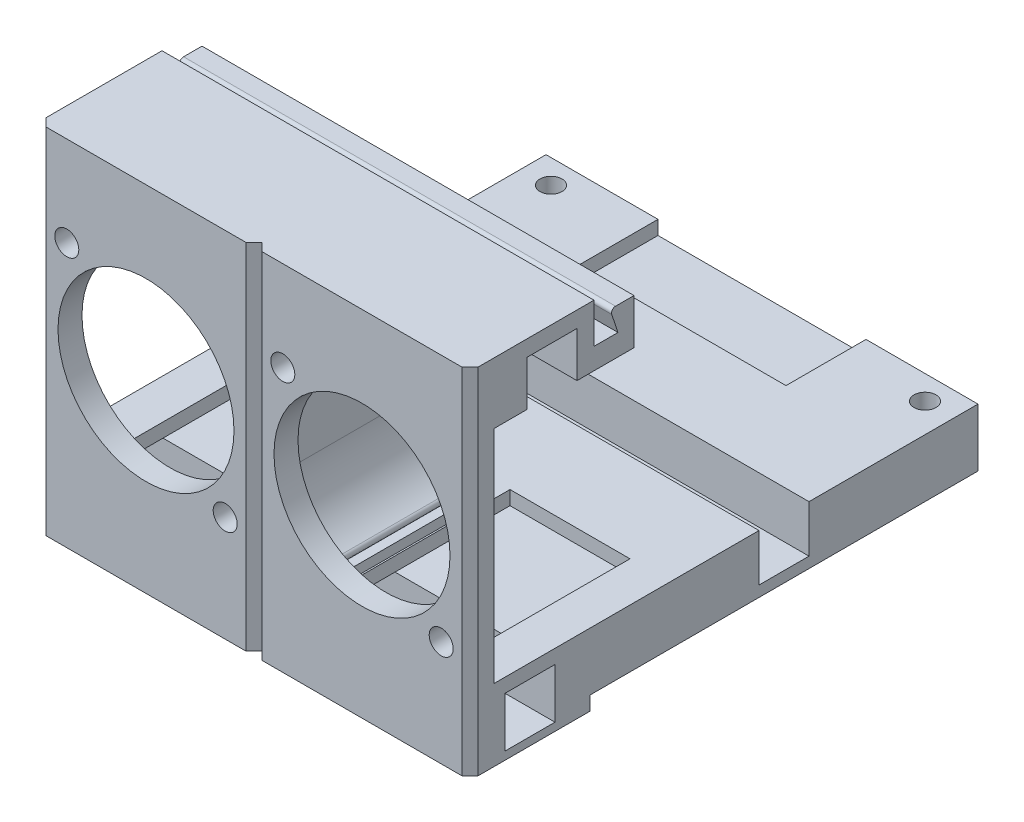
SolidWorks part; units mm, degrees
ref_plane "Front Plane" through (0, 0, 0) normal (0, 0, 1) x (1, 0, 0)
ref_plane "Top Plane" through (0, 0, 0) normal (0, 1, 0) x (1, 0, 0)
ref_plane "Right Plane" through (0, 0, 0) normal (1, 0, 0) x (0, 0, -1)
sketch "Sketch1" plane through (0, 0, 0) normal (0, 1, 0) x (1, 0, 0)
  line L0 (-23.375, 28.75) -> (23.375, 28.75) construction
  line L1 (-27, 31.75) -> (27, 31.75)
  line L2 (-27, 31.75) -> (-27, -31.75)
  line L3 (-27, -31.75) -> (27, -31.75)
  line L4 (27, 31.75) -> (27, -31.75)
  line L5 (-27, 31.75) -> (27, -31.75) construction
  line L6 (-27, -31.75) -> (27, 31.75) construction
  line L11 (0, 0) -> (0, 28.75) construction
  circle A0 centre (-23.375, 28.75) radius 1.375
  circle A1 centre (23.375, 28.75) radius 1.375
  circle A2 centre (0, -5.5) radius 1.375
  point P0 (0, 0)
  dimension "D3" = 2.75
  dimension "D1" = 54
  dimension "D2" = 63.5
  dimension "D4" = 3
  dimension "D5" = 46.75
  dimension "D6" = 34.25
extrude "Boss-Extrude1" add sketch "Sketch1" along normal blind 9
sketch "Sketch2" plane through (0, 9, 0) normal (0, 1, 0) x (1, 0, 0)
  line L0 (27, -31.75) -> (27, 31.75) construction
  line L1 (-27, -31.75) -> (27, -31.75)
  line L2 (-27, -31.75) -> (-27, -28.75)
  line L3 (-27, -28.75) -> (27, -28.75)
  line L4 (27, -31.75) -> (27, -28.75)
  dimension "D1" = 3
extrude "Boss-Extrude2" add sketch "Sketch2" along normal offset from surface (35.25 mm away) 44.25 up to face at (0, 0, 0)
sketch "Sketch3" plane through (0, 0, 31.75) normal (0, 0, 1) x (1, 0, 0)
  line L0 (-27, 9) -> (27, 9) construction
  line L1 (-27, 44.25) -> (-27, 0) construction
  line L2 (27, 44.25) -> (27, 0) construction
  line L3 (0, 10.6) -> (0, 23.1) construction
  line L4 (-27, 10.6) -> (27, 10.6) construction
  line L5 (-23.4, 33) -> (-3.6, 33) construction
  line L6 (-23.4, 33) -> (-23.4, 13.2) construction
  line L7 (-23.4, 13.2) -> (-3.6, 13.2) construction
  line L8 (-3.6, 33) -> (-3.6, 13.2) construction
  line L9 (-23.4, 33) -> (-3.6, 13.2) construction
  line L10 (-23.4, 13.2) -> (-3.6, 33) construction
  line L11 (3.6, 33) -> (23.4, 33) construction
  line L12 (3.6, 33) -> (3.6, 13.2) construction
  line L13 (3.6, 13.2) -> (23.4, 13.2) construction
  line L14 (23.4, 33) -> (23.4, 13.2) construction
  line L15 (3.6, 33) -> (23.4, 13.2) construction
  line L16 (3.6, 13.2) -> (23.4, 33) construction
  line L17 (-2.5, 23.1) -> (-3.6, 23.1) construction
  line L18 (2.5, 23.1) -> (3.6, 23.1) construction
  line L21 (27, 9) -> (-27, 9) construction
  line L22 (-2.5, 23.1) -> (2.5, 23.1) construction
  circle A0 centre (-13.5, 23.1) radius 11
  circle A1 centre (13.5, 23.1) radius 11
  circle A2 centre (-23.4, 33) radius 1.5
  circle A3 centre (-3.6, 13.2) radius 1.5
  circle A4 centre (3.6, 33) radius 1.5
  circle A5 centre (23.4, 13.2) radius 1.5
  point P6 (-13.5, 23.1)
  point P13 (13.5, 23.1)
  dimension "D1" = 3
  dimension "D2" = 22
  dimension "D3" = 19.8
  dimension "D4" = 19.8
  dimension "D5" = 12.5
  dimension "D6" = 1.6
  dimension "D7" = 13.5
  dimension "D8" = 13.5
extrude "Cut-Extrude1" cut sketch "Sketch3" against normal through all
sketch "Sketch4" plane through (0, 0, 0) normal (0, -1, 0) x (-1, 0, 0)
  line L0 (-27, -31.75) -> (-27, 31.75) construction
  line L1 (27, 31.75) -> (-27, 31.75)
  line L2 (27, 31.75) -> (27, -16.75)
  line L3 (27, -16.75) -> (-27, -16.75)
  line L4 (-27, 31.75) -> (-27, -16.75)
  line L5 (27, -31.75) -> (-27, -31.75) construction
  dimension "D1" = 15
extrude "Cut-Extrude2" cut sketch "Sketch4" against normal blind 1.75
sketch "Sketch5" plane through (0, 0, 28.75) normal (0, 0, -1) x (-1, 0, 0)
  line L0 (-13.5, 23.1) -> (13.5, 23.1) construction
  line L1 (0, 9) -> (0, 23.1) construction
  line L2 (-1.25, 23.1) -> (-1.25, 29.8413)
  line L3 (-27, 9) -> (27, 9) construction
  line L15 (-13.5, 23.1) -> (-13.5, 34.1) construction
  line L16 (13.5, 23.1) -> (13.5, 34.1) construction
  line L17 (-13.5, 25.9095) -> (13.5, 25.9095) construction
  line L18 (-1.25, 23.1) -> (-1.25, 19.35)
  line L19 (-5.8167, 10.6) -> (0, 10.6)
  line L20 (1.5, 23.1) -> (1.5, 16.8865)
  line L21 (0, 10.6) -> (0.6, 10.6)
  line L22 (0.6, 10.6) -> (0.6, 13.2)
  line L23 (0.6, 13.2) -> (3.6, 13.2) construction
  line L24 (-1.25, 23.1) -> (0, 23.1) construction
  line L25 (1.5, 23.1) -> (1.5, 25.3221)
  line L26 (9.4, 36.6) -> (-0.6, 36.6)
  line L27 (-0.6, 36.6) -> (-0.6, 33)
  line L28 (-3.6, 33) -> (-0.6, 33) construction
  line L29 (0, 23.1) -> (1.5, 23.1) construction
  arc A13 (-0.8437, 31.8155) -> (-0.6, 33) centre (-3.6, 33) ccw
  circle A16 centre (13.5, 23.1) radius 11 construction
  circle A17 centre (-13.5, 23.1) radius 11 construction
  arc A18 (6.5989, 13.283) -> (23.317, 30.0011) centre (13.5, 23.1) ccw construction
  arc A19 (23.317, 30.0011) -> (20.4011, 32.917) centre (23.4, 33) ccw construction
  arc A20 (3.683, 16.1989) -> (1.5, 15.3424) centre (3.6, 13.2) ccw construction
  arc A21 (3.683, 16.1989) -> (6.5989, 13.283) centre (13.5, 23.1) ccw construction
  arc A22 (6.5989, 13.283) -> (3.683, 16.1989) centre (3.6, 13.2) ccw construction
  arc A23 (20.4011, 32.917) -> (1.8335, 25.9095) centre (13.5, 23.1) ccw construction
  arc A24 (23.317, 30.0011) -> (20.4011, 32.917) centre (13.5, 23.1) ccw construction
  arc A25 (20.4011, 32.917) -> (23.317, 30.0011) centre (23.4, 33) ccw construction
  arc A26 (-6.0428, 11.5459) -> (-1.25, 19.35) centre (-10, 19.35) ccw
  arc A27 (1.5, 23.1) -> (3.683, 16.1989) centre (13.5, 23.1) ccw construction
  arc A28 (1.8335, 25.9095) -> (1.5, 23.1) centre (13.5, 23.1) ccw construction
  arc A29 (0.6, 13.2) -> (6.5989, 13.283) centre (3.6, 13.2) ccw construction
  arc A30 (0.9375, 14.5824) -> (0.6, 13.2) centre (3.6, 13.2) ccw
  arc A31 (1.5, 16.8865) -> (0.9375, 14.5824) centre (-3.5, 16.8865) cw
  arc A32 (-5.8167, 10.6) -> (-6.0428, 11.5459) centre (-5.8167, 11.1) cw
  arc A33 (-0.6, 33) -> (-1.25, 31.1352) centre (-3.6, 33) ccw construction
  arc A34 (-1.25, 29.8413) -> (-0.8437, 31.8155) centre (3.75, 29.8413) cw
  arc A37 (9.4, 36.6) -> (1.5, 25.3221) centre (13.5, 25.3221) ccw
  point P28 (3.5, 32.5868)
  point P29 (-8, 32.5868)
  point P30 (2.5213, 27.9443)
  point P40 (-10, 10.6)
  point P62 (9.4, 36.6)
  dimension "D2" = 3
  dimension "D4" = 1.6
  dimension "D1" = 3
  dimension "D3" = 12
  dimension "D6" = 10
  dimension "D7" = 5
  dimension "D8" = 0.5
  dimension "D9" = 5
  dimension "D5" = 12.25
  dimension "D10" = 10
  dimension "D11" = 13.5
extrude "Boss-Extrude3" add sketch "Sketch5" along normal blind 17.5
sketch "Sketch6" plane through (0, 0, 28.75) normal (0, 0, -1) x (-1, 0, 0)
  line L0 (27, 44.25) -> (27, 9) construction
  line L1 (-27, 44.25) -> (27, 44.25)
  line L2 (-27, 44.25) -> (-27, 36.6)
  line L3 (-27, 36.6) -> (27, 36.6)
  line L4 (27, 44.25) -> (27, 36.6)
  point P7 (-0.6, 36.6)
extrude "Boss-Extrude5" add sketch "Sketch6" along normal up to surface (17.5 mm away) up to face at (0.2231, 22.3398, 11.25)
fillet "Fillet2" radius 3 2 edges at (-9.4, 36.6, 20) (0.6, 36.6, 20)
sketch "Sketch8" plane through (0, 9, 0) normal (0, 1, 0) x (1, 0, 0)
  line L0 (27, -28.75) -> (-27, -28.75) construction
  line L1 (22, -28.75) -> (7, -28.75)
  line L2 (22, -28.75) -> (22, -6.75)
  line L3 (22, -6.75) -> (7, -6.75)
  line L4 (-22, -28.75) -> (-22, -6.75)
  line L5 (27, -28.75) -> (27, 31.75) construction
  line L6 (0, 0) -> (0, -6.75) construction
  line L7 (-7, -6.75) -> (-22, -6.75)
  line L8 (27, 31.75) -> (-27, 31.75) construction
  line L9 (-13, 31.75) -> (13, 31.75)
  line L10 (-13, 31.75) -> (-13, 21.75)
  line L11 (-13, 21.75) -> (13, 21.75)
  line L12 (13, 31.75) -> (13, 21.75)
  line L13 (0, 0) -> (0, 21.75) construction
  line L14 (7, -6.75) -> (7, -28.75)
  line L16 (-7, -6.75) -> (-7, -28.75)
  line L17 (-27, 31.75) -> (-27, -28.75) construction
  line L18 (-7, -28.75) -> (-22, -28.75)
  dimension "D3" = 7
  dimension "D1" = 5
  dimension "D2" = 22
  dimension "D4" = 26
  dimension "D5" = 10
  dimension "D6" = 7
  dimension "D7" = 5
extrude "Cut-Extrude4" cut sketch "Sketch8" against normal blind 1.75
sketch "Sketch7" plane through (27, 0, 0) normal (1, 0, 0) x (0, 0, -1)
  line L0 (-31.75, 0) -> (-16.75, 0) construction
  line L1 (7.5, 1.75) -> (7.5, 9) construction
  line L2 (-28.75, 9) -> (31.75, 9) construction
  line L3 (-24.25, 9) -> (-24.25, 36.6) construction
  line L4 (-11.25, 36.6) -> (-28.75, 36.6) construction
  line L5 (-24.25, 36.6) -> (-24.25, 44.25) construction
  line L6 (-31.75, 44.25) -> (-11.25, 44.25) construction
  line L7 (31.75, 1.75) -> (-16.75, 1.75) construction
  line L14 (-24.25, 9) -> (-24.25, 0) construction
  line L15 (-27.375, 7.25) -> (-21.125, 7.25)
  line L16 (-27.375, 7.25) -> (-27.375, 1)
  line L17 (-27.375, 1) -> (-21.125, 1)
  line L18 (-21.125, 7.25) -> (-21.125, 1)
  line L19 (-27.375, 7.25) -> (-21.125, 1) construction
  line L20 (-27.375, 1) -> (-21.125, 7.25) construction
  line L21 (-24.625, 36) -> (-18.375, 36)
  line L22 (-24.625, 36) -> (-24.625, 42.25)
  line L23 (-24.625, 42.25) -> (-18.375, 42.25)
  line L24 (-18.375, 36) -> (-18.375, 42.25)
  line L25 (-24.625, 36) -> (-18.375, 42.25) construction
  line L26 (-24.625, 42.25) -> (-18.375, 36) construction
  line L27 (-21.5, 44.25) -> (-21.5, 39.125) construction
  line L28 (-6.75, 7.25) -> (-28.75, 7.25) construction
  line L29 (4.375, 3.1) -> (10.625, 3.1)
  line L30 (4.375, 3.1) -> (4.375, 9)
  line L31 (4.375, 9) -> (10.625, 9)
  line L32 (10.625, 3.1) -> (10.625, 9)
  line L33 (4.375, 3.1) -> (10.625, 9) construction
  line L34 (4.375, 9) -> (10.625, 3.1) construction
  point P0 (-21.5, 39.125)
  point P18 (-24.25, 4.125)
  point P20 (7.5, 6.05)
  dimension "D1" = 5.9
  dimension "D2" = 2
  dimension "D3" = 6.25
extrude "Cut-Extrude3" cut sketch "Sketch7" against normal through all
chamfer "Chamfer2" distance 1 angle 45 2 edges at (-27, 22.125, 31.75) (27, 22.125, 31.75)
sketch "Sketch9" plane through (0, 44.25, 0) normal (0, 1, 0) x (1, 0, 0)
  line L0 (0, -31.75) -> (0, -30.75) construction
  line L1 (-26, -31.75) -> (26, -31.75) construction
  line L2 (-1, -31.75) -> (0, -30.75)
  line L3 (0, -30.75) -> (1, -31.75)
  line L4 (1, -31.75) -> (-1, -31.75)
  line L5 (-27, -30.75) -> (-26, -31.75) construction
extrude "Cut-Extrude5" cut sketch "Sketch9" against normal through all
sketch "Sketch10" plane through (27, 0, 0) normal (1, 0, 0) x (0, 0, -1)
  line L0 (-11.25, 44.25) -> (-16.25, 44.25)
  line L1 (-30.75, 44.25) -> (-11.25, 44.25) construction
  line L2 (-16.25, 44.25) -> (-16.25, 39.25)
  line L3 (-16.25, 39.25) -> (-13.25, 39.25)
  line L4 (-13.25, 39.25) -> (-14.0306, 41.5919)
  line L5 (-13.5563, 42.25) -> (-11.25, 42.25)
  line L6 (-11.25, 44.25) -> (-11.25, 36.6) construction
  line L7 (-11.25, 42.25) -> (-11.25, 44.25)
  arc A0 (-14.0306, 41.5919) -> (-13.5563, 42.25) centre (-13.5563, 41.75) cw
  point P13 (-14.25, 42.25)
  dimension "D6" = 0.5
  dimension "D1" = 5
  dimension "D2" = 2
  dimension "D3" = 2
  dimension "D4" = 5
  dimension "D5" = 2
extrude "Cut-Extrude6" cut sketch "Sketch10" against normal through all
sketch "Sketch13" plane through (0, 9, 0) normal (0, 1, 0) x (1, 0, 0)
  line L0 (7, -6.75) -> (7, -28.75) construction
  line L1 (7, -28.3698) -> (-1.6809, -28.3698)
  line L2 (7, -28.3698) -> (7, -10.1957)
  line L3 (7, -10.1957) -> (-1.6809, -10.1957)
  line L4 (-1.6809, -28.3698) -> (-1.6809, -10.1957)
extrude "Boss-Extrude6" add sketch "Sketch13" along normal offset from surface (1.2 mm away) 0.2 from offset 0.2 separate body up to face at (2.6083, 10.6, 20)
